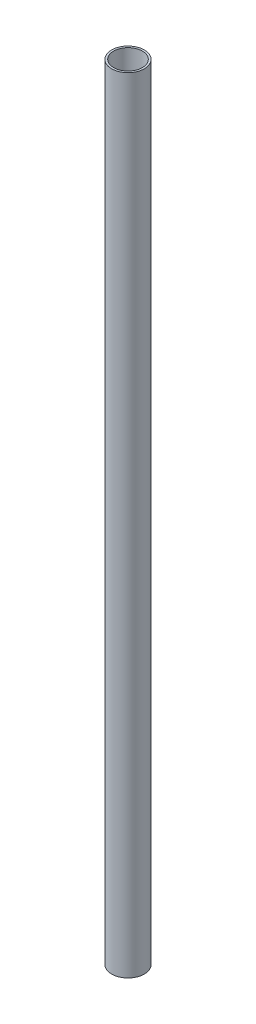
SolidWorks part; units mm, degrees
ref_plane "前视基准面" through (0, 0, 0) normal (0, 0, 1) x (1, 0, 0)
ref_plane "上视基准面" through (0, 0, 0) normal (0, 1, 0) x (1, 0, 0)
ref_plane "右视基准面" through (0, 0, 0) normal (1, 0, 0) x (0, 0, -1)
sketch "草图2" plane through (0, 0, 0) normal (0, 1, 0) x (1, 0, 0)
  circle A0 centre (0, 0) radius 12.5
  circle A1 centre (0, 0) radius 11
  dimension "D1" = 25
  dimension "D2" = 22
extrude "凸台-拉伸1" add sketch "草图2" along normal mid plane 600
